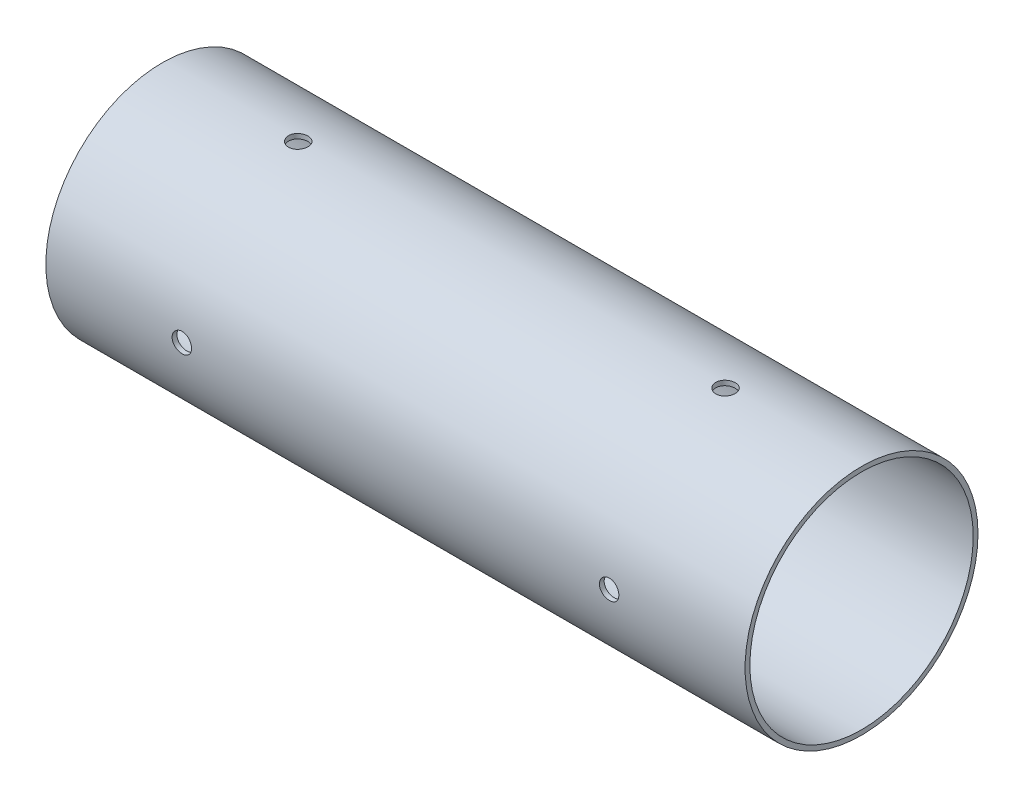
SolidWorks part; units mm, degrees
ref_plane "Front Plane" through (0, 0, 0) normal (1, 0, 0) x (0, 1, 0)
ref_plane "Top Plane" through (0, 0, 0) normal (0, 0, 1) x (0, 1, 0)
ref_plane "Right Plane" through (0, 0, 0) normal (0, 1, 0) x (-1, 0, 0)
sketch "Sketch1" plane through (0, 0, 0) normal (1, 0, 0) x (0, 1, 0)
  circle A0 centre (0, 0) radius 36.5125
  circle A1 centre (0, 0) radius 38.0746
  dimension "D1" = 76.1492
  dimension "D2" = 73.025
extrude "Boss-Extrude1" add sketch "Sketch1" along normal blind 228.6
sketch "Sketch2" plane through (0, 0, 0) normal (0, 1, 0) x (-1, 0, 0)
  line L0 (-228.6, 38.0746) -> (-228.6, -38.0746) construction
  circle A0 centre (-184.15, 0) radius 3.175
  dimension "D2" = 6.35
  dimension "D1" = 44.45
extrude "Cut-Extrude1" cut sketch "Sketch2" against normal through all
pattern_circular "CirPattern1" count 4 over 360 about axis through (228.6, 0, 0) along (-1, 0, 0) of "Cut-Extrude1"
sketch "Sketch3" plane through (0, 0, 0) normal (0, 1, 0) x (-1, 0, 0)
  line L0 (0, -38.0746) -> (0, 38.0746) construction
  circle A0 centre (-44.45, 0) radius 3.175
  dimension "D1" = 6.35
  dimension "D2" = 44.45
extrude "Cut-Extrude2" cut sketch "Sketch3" against normal through all
pattern_circular "CirPattern2" count 4 over 360 about axis through (228.6, 0, 0) along (-1, 0, 0) of "Cut-Extrude2"
